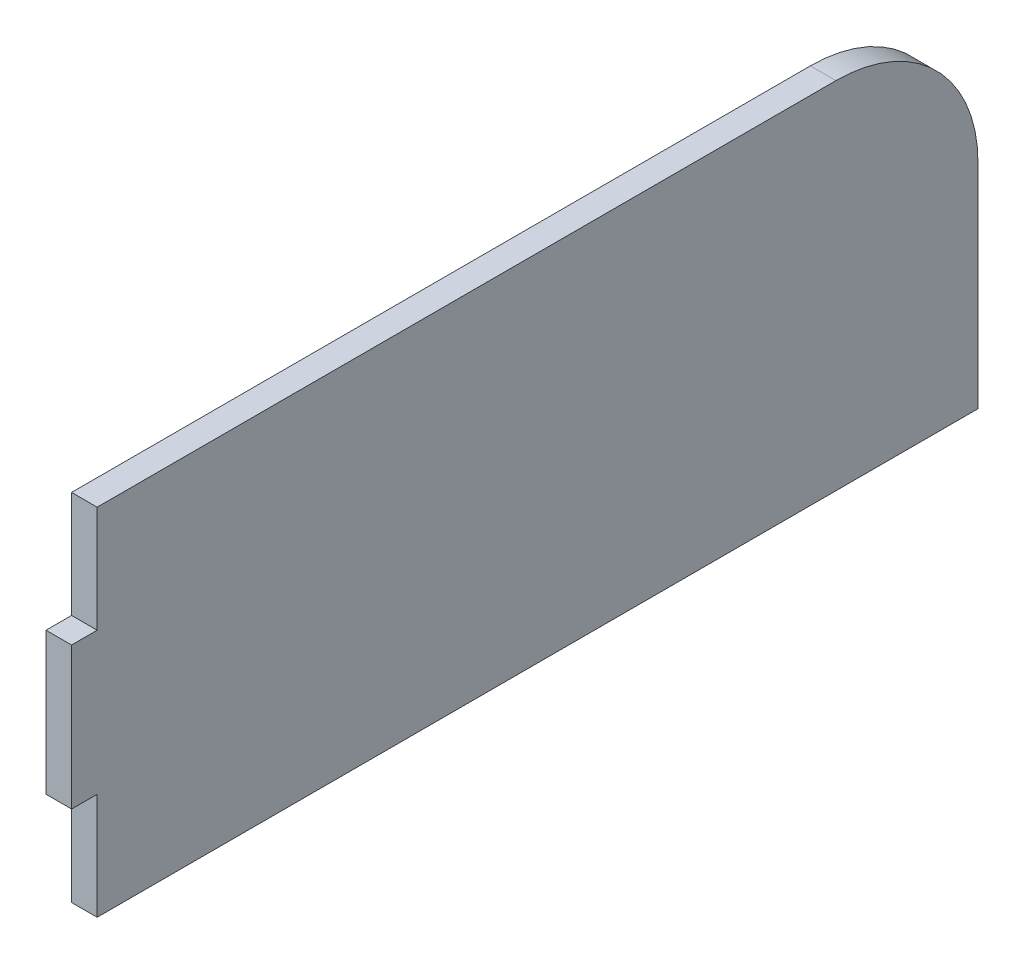
SolidWorks part; units mm, degrees
ref_plane "Front Plane" through (0, 0, 0) normal (0, 0, 1) x (1, 0, 0)
ref_plane "Top Plane" through (0, 0, 0) normal (0, 1, 0) x (1, 0, 0)
ref_plane "Right Plane" through (0, 0, 0) normal (1, 0, 0) x (0, 0, -1)
sketch "Sketch1" plane through (0, 0, 0) normal (1, 0, 0) x (0, 0, -1)
  line L0 (0, -175) -> (0, -250)
  line L1 (0, 0) -> (520, 0)
  line L2 (0, 0) -> (0, -75)
  line L3 (0, -250) -> (620, -250)
  line L4 (620, -100) -> (620, -250)
  line L5 (0, -75) -> (-18, -75)
  line L7 (0, -175) -> (-18, -175)
  line L8 (-18, -75) -> (-18, -175)
  arc A0 (620, -100) -> (520, 0) centre (520, -100) ccw
  point P7 (620, 0)
  point P8 (0, -125)
  dimension "D3" = 100
  dimension "D1" = 250
  dimension "D2" = 620
  dimension "D5" = 100
extrude "Boss-Extrude1" add sketch "Sketch1" along normal blind 18
